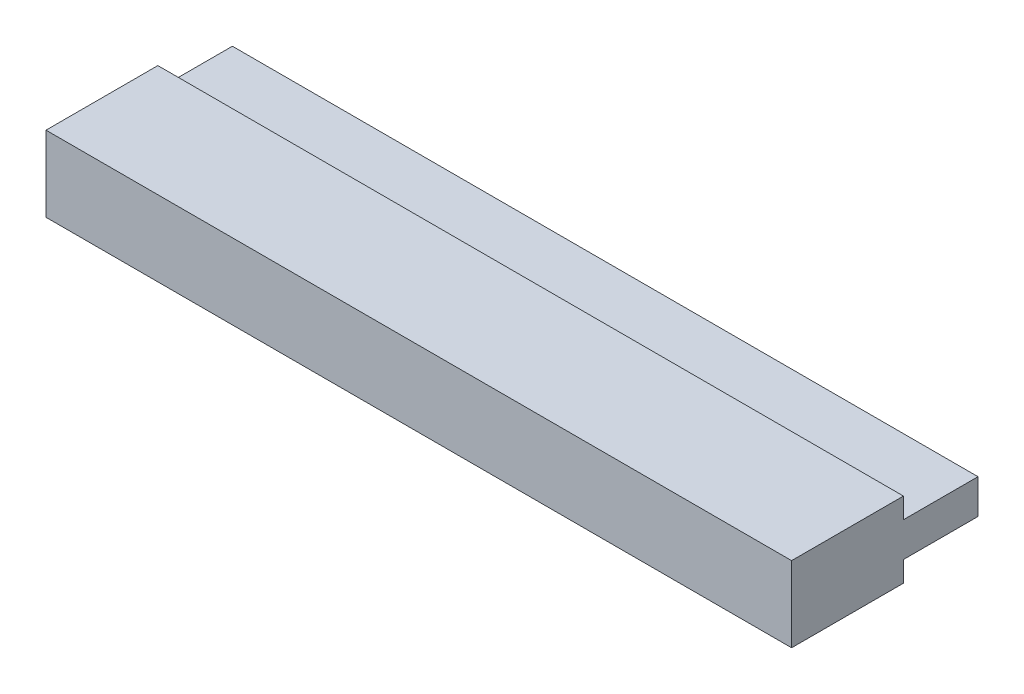
SolidWorks part; units mm, degrees
ref_plane "Alzado" through (0, 0, 0) normal (0, 0, 1) x (1, 0, 0)
ref_plane "Planta" through (0, 0, 0) normal (0, 1, 0) x (1, 0, 0)
ref_plane "Vista lateral" through (0, 0, 0) normal (1, 0, 0) x (0, 0, -1)
sketch "Sketch1" plane through (0, 0, 0) normal (0, 0, 1) x (1, 0, 0)
  line L1 (0, 0) -> (80, 0)
  line L2 (0, 0) -> (0, 8.1)
  line L3 (0, 8.1) -> (80, 8.1)
  line L4 (80, 0) -> (80, 8.1)
  dimension "D1" = 8.1
  dimension "D2" = 80
extrude "Boss-Extrude1" add sketch "Sketch1" along normal blind 20
sketch "Sketch2" plane through (0, 0, 0) normal (-1, 0, 0) x (0, 0, 1)
  line L0 (20, 0) -> (0, 0) construction
  line L1 (0, 8.1) -> (8, 8.1)
  line L2 (0, 8.1) -> (0, 5.9)
  line L3 (0, 0) -> (8, 0)
  line L4 (8, 8.1) -> (8, 5.9)
  line L5 (8, 5.9) -> (1.0065, 5.9)
  line L7 (1.0065, 2.2) -> (8, 2.2)
  line L8 (8, 2.2) -> (8, 0)
  line L9 (1.0065, 5.9) -> (0, 5.9)
  line L10 (1.0065, 2.2) -> (0, 2.2)
  line L11 (0, 2.2) -> (0, 0)
  dimension "D1" = 8
  dimension "D2" = 2.2
  dimension "D3" = 2.2
extrude "Cut-Extrude1" cut sketch "Sketch2" against normal blind 85
